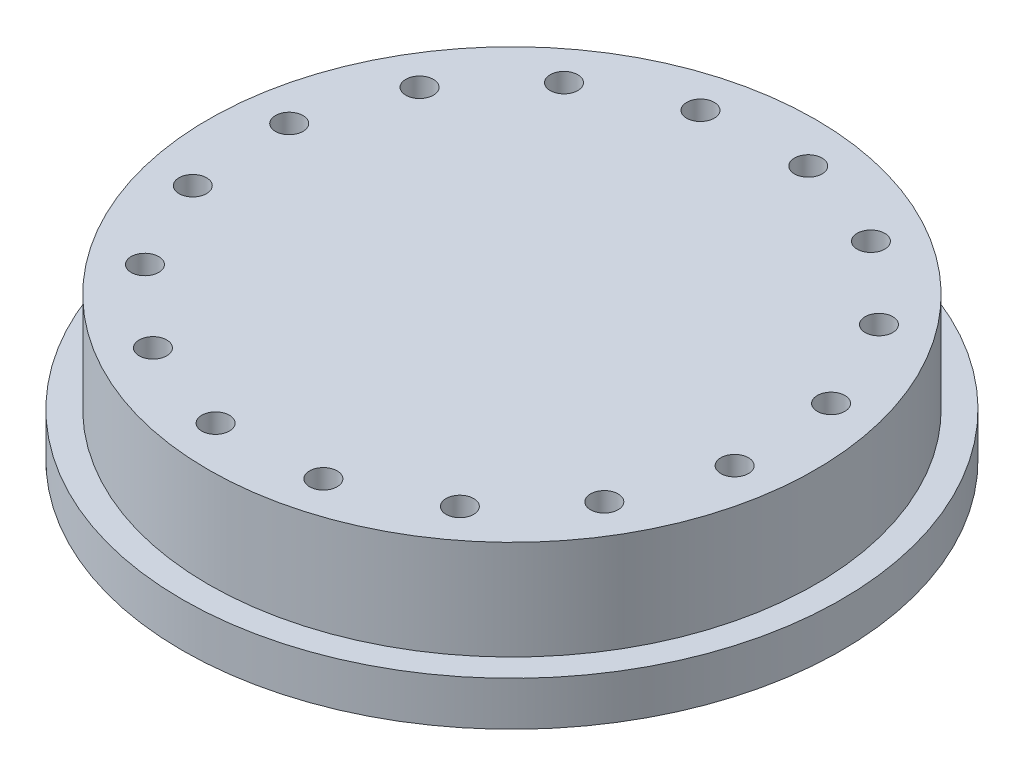
SolidWorks part; units mm, degrees
material "6061-T6 (SS)"
ref_plane "Front Plane" through (0, 0, 0) normal (0, 0, 1) x (1, 0, 0)
ref_plane "Top Plane" through (0, 0, 0) normal (0, 1, 0) x (1, 0, 0)
ref_plane "Right Plane" through (0, 0, 0) normal (1, 0, 0) x (0, 0, -1)
sketch "Sketch1" plane through (0, 0, 0) normal (0, 1, 0) x (1, 0, 0)
  circle A0 centre (0, 0) radius 29.8611
  dimension "D1" = 59.7222
extrude "Boss-Extrude1" add sketch "Sketch1" along normal mid plane 4
sketch "Sketch2" plane through (0, 2, 0) normal (0, 1, 0) x (1, 0, 0)
  circle A0 centre (0, 0) radius 27.5
  dimension "D1" = 55
extrude "Boss-Extrude2" add sketch "Sketch2" along normal blind 9
sketch "Sketch3" plane through (0, -2, 0) normal (0, -1, 0) x (1, 0, 0)
  circle A0 centre (23.001, -5.9177) radius 1.25 construction
  circle A1 centre (23.5147, 3.3349) radius 1.25 construction
  circle A2 centre (20.4485, 12.0797) radius 1.25 construction
  circle A3 centre (14.2693, 18.9855) radius 1.25 construction
  circle A4 centre (18.9855, -14.2693) radius 1.25 construction
  circle A5 centre (5.9177, 23.001) radius 1.25 construction
  circle A6 centre (-3.3349, 23.5147) radius 1.25 construction
  circle A7 centre (-12.0797, 20.4485) radius 1.25 construction
  circle A8 centre (-18.9855, 14.2693) radius 1.25 construction
  circle A9 centre (-23.001, 5.9177) radius 1.25 construction
  circle A10 centre (-23.5147, -3.3349) radius 1.25 construction
  circle A11 centre (12.0797, -20.4485) radius 1.25 construction
  circle A12 centre (3.3349, -23.5147) radius 1.25 construction
  circle A13 centre (-5.9177, -23.001) radius 1.25 construction
  circle A14 centre (-14.2693, -18.9855) radius 1.25 construction
  circle A15 centre (-20.4485, -12.0797) radius 1.25 construction
  circle A16 centre (23.001, -5.9177) radius 1.25
  circle A17 centre (23.5147, 3.3349) radius 1.25
  circle A18 centre (20.4485, 12.0797) radius 1.25
  circle A19 centre (14.2693, 18.9855) radius 1.25
  circle A20 centre (18.9855, -14.2693) radius 1.25
  circle A21 centre (5.9177, 23.001) radius 1.25
  circle A22 centre (-3.3349, 23.5147) radius 1.25
  circle A23 centre (-12.0797, 20.4485) radius 1.25
  circle A24 centre (-18.9855, 14.2693) radius 1.25
  circle A25 centre (-23.001, 5.9177) radius 1.25
  circle A26 centre (-23.5147, -3.3349) radius 1.25
  circle A27 centre (12.0797, -20.4485) radius 1.25
  circle A28 centre (3.3349, -23.5147) radius 1.25
  circle A29 centre (-5.9177, -23.001) radius 1.25
  circle A30 centre (-14.2693, -18.9855) radius 1.25
  circle A31 centre (-20.4485, -12.0797) radius 1.25
extrude "Cut-Extrude1" cut sketch "Sketch3" against normal through all both and the other way through all
